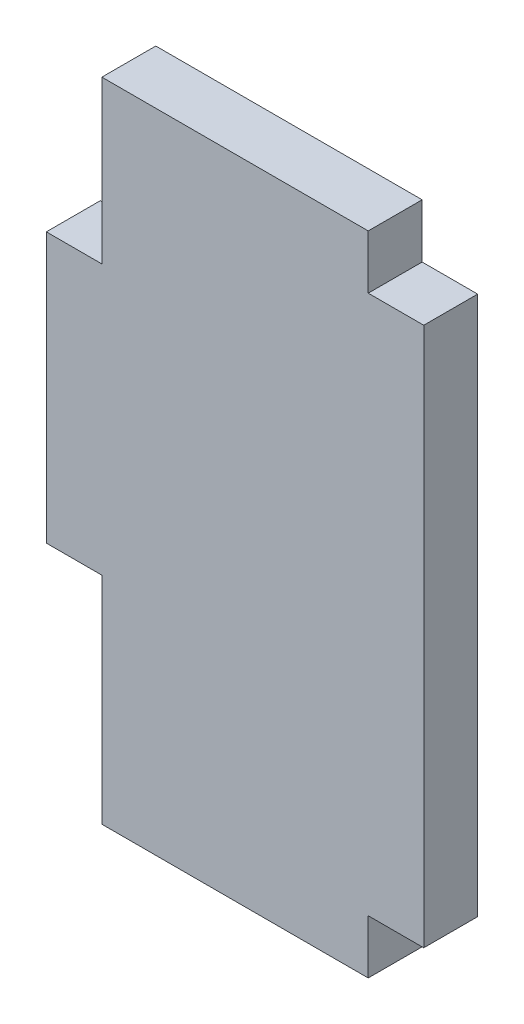
SolidWorks part; units mm, degrees
ref_plane "Front Plane" through (0, 0, 0) normal (0, 0, 1) x (1, 0, 0)
ref_plane "Top Plane" through (0, 0, 0) normal (0, 1, 0) x (1, 0, 0)
ref_plane "Right Plane" through (0, 0, 0) normal (1, 0, 0) x (0, 0, -1)
sketch "Sketch1" plane through (0, 0, 0) normal (0, 0, 1) x (1, 0, 0)
  line L0 (-5.15, 45) -> (0, 45)
  line L2 (-5.15, 45) -> (-5.15, 20)
  line L4 (29.85, 55) -> (29.85, 5)
  line L5 (0, 45) -> (0, 60)
  line L6 (0, 60) -> (24.7, 60)
  line L7 (24.7, 60) -> (24.7, 55)
  line L8 (24.7, 55) -> (29.85, 55)
  line L9 (-5.15, 20) -> (0, 20)
  line L10 (0, 20) -> (0, 0)
  line L11 (0, 0) -> (24.7, 0)
  line L12 (24.7, 0) -> (24.7, 5)
  line L13 (24.7, 5) -> (29.85, 5)
  point P1 (0, 0)
  point P5 (-5.15, 40)
  point P11 (29.8412, 38.8896)
  point P12 (18.0838, -23.1958)
  dimension "D1" = 25
  dimension "D2" = 35
  dimension "D3" = 24.7
  dimension "D4" = 15
  dimension "D5" = 5
  dimension "D6" = 20
  dimension "D7" = 5
extrude "Boss-Extrude1" add sketch "Sketch1" along normal blind 5
